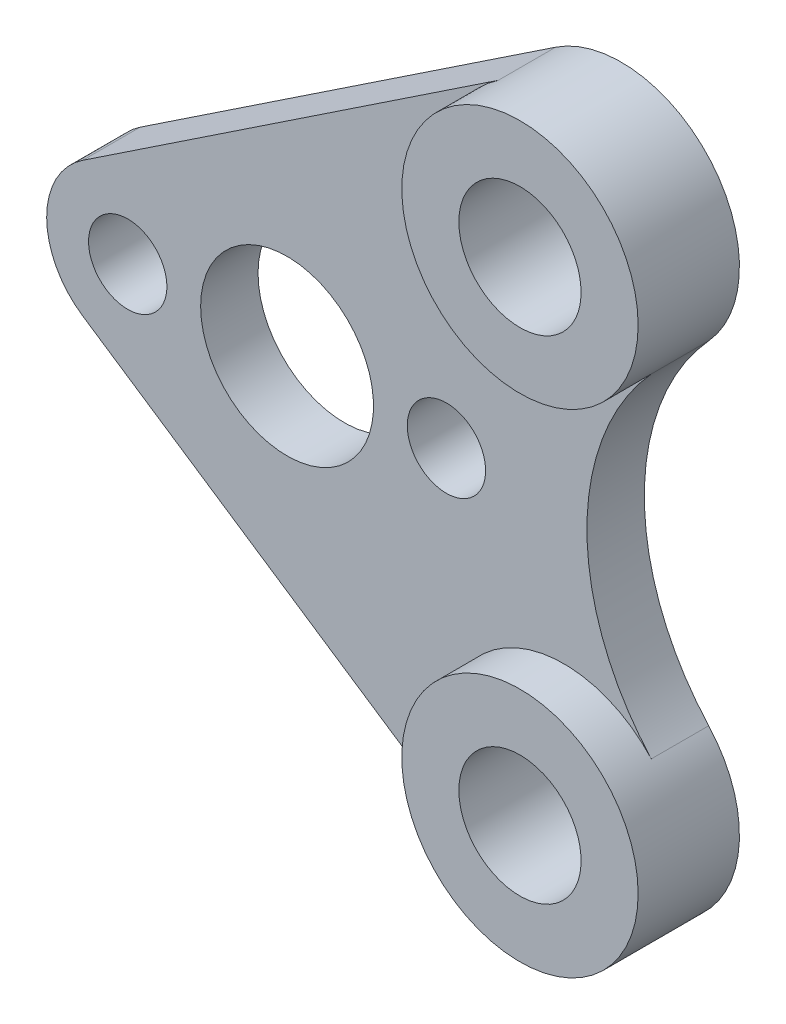
SolidWorks part; units mm, degrees
ref_plane "Front Plane" through (0, 0, 0) normal (0, 0, 1) x (1, 0, 0)
ref_plane "Top Plane" through (0, 0, 0) normal (0, 1, 0) x (1, 0, 0)
ref_plane "Right Plane" through (0, 0, 0) normal (1, 0, 0) x (0, 0, -1)
sketch "Sketch1" plane through (0, 0, 0) normal (0, 0, 1) x (1, 0, 0)
  line L0 (0, 5.1219) -> (0, -5.1219) construction
  line L1 (0, 0) -> (13.2766, 0) construction
  line L2 (7.9449, 12.9567) -> (-7.6852, 2.536)
  line L3 (-7.6852, -2.536) -> (7.9449, -12.9567)
  circle A0 centre (0, 0) radius 3.2512
  circle A1 centre (-5.9944, 0) radius 1.4732
  circle A2 centre (5.9944, 0) radius 1.4732
  circle A3 centre (10.4107, 9.2583) radius 2.2987
  circle A4 centre (10.4107, -9.2583) radius 2.2987
  arc A5 (-7.6852, 2.536) -> (-7.6852, -2.536) centre (-5.9944, 0) ccw
  arc A6 (7.9449, -12.9567) -> (13.7004, -6.2691) centre (10.4107, -9.2583) ccw
  arc A7 (13.7004, 6.2691) -> (7.9449, 12.9567) centre (10.4107, 9.2583) ccw
  arc A8 (13.7004, 6.2691) -> (13.7004, -6.2691) centre (20.5997, 0) ccw
  point P9 (0, 0)
  point P24 (0, 0)
  dimension "D1" = 2.9464
  dimension "D2" = 6.5024
  dimension "D3" = 9.0424
  dimension "D4" = 4.5974
  dimension "D5" = 23.114
  dimension "D6" = 8.382
  dimension "D7" = 4.445
  dimension "D8" = 3.048
  dimension "D9" = 3.81
extrude "Boss-Extrude1" add sketch "Sketch1" along normal blind 3.81
sketch "Sketch2" plane through (0, 0, 3.81) normal (0, 0, 1) x (1, 0, 0)
  line L2 (7.9449, 12.9567) -> (-7.6852, 2.536)
  line L3 (-7.6852, -2.536) -> (7.9449, -12.9567)
  line L4 (7.9449, 12.9567) -> (-7.6852, 2.536)
  line L5 (-7.6852, -2.536) -> (7.9449, -12.9567)
  arc A0 (7.9449, 12.9567) -> (13.7004, 6.2691) centre (10.4107, 9.2583) ccw
  arc A1 (13.7004, -6.2691) -> (7.9449, -12.9567) centre (10.4107, -9.2583) ccw
  arc A4 (13.7004, 6.2691) -> (7.9449, 12.9567) centre (10.4107, 9.2583) ccw
  arc A5 (-7.6852, 2.536) -> (-7.6852, -2.536) centre (-5.9944, 0) ccw
  arc A6 (7.9449, -12.9567) -> (13.7004, -6.2691) centre (10.4107, -9.2583) ccw
  arc A7 (13.7004, 6.2691) -> (13.7004, -6.2691) centre (20.5997, 0) ccw
  arc A9 (-7.6852, 2.536) -> (-7.6852, -2.536) centre (-5.9944, 0) ccw
  arc A11 (13.7004, 6.2691) -> (13.7004, -6.2691) centre (20.5997, 0) ccw
  dimension "D1" = 0
extrude "Cut-Extrude2" cut sketch "Sketch2" against normal offset from surface (1.651 mm away) 2.159 up to face at (5.0091, 0, 0)
